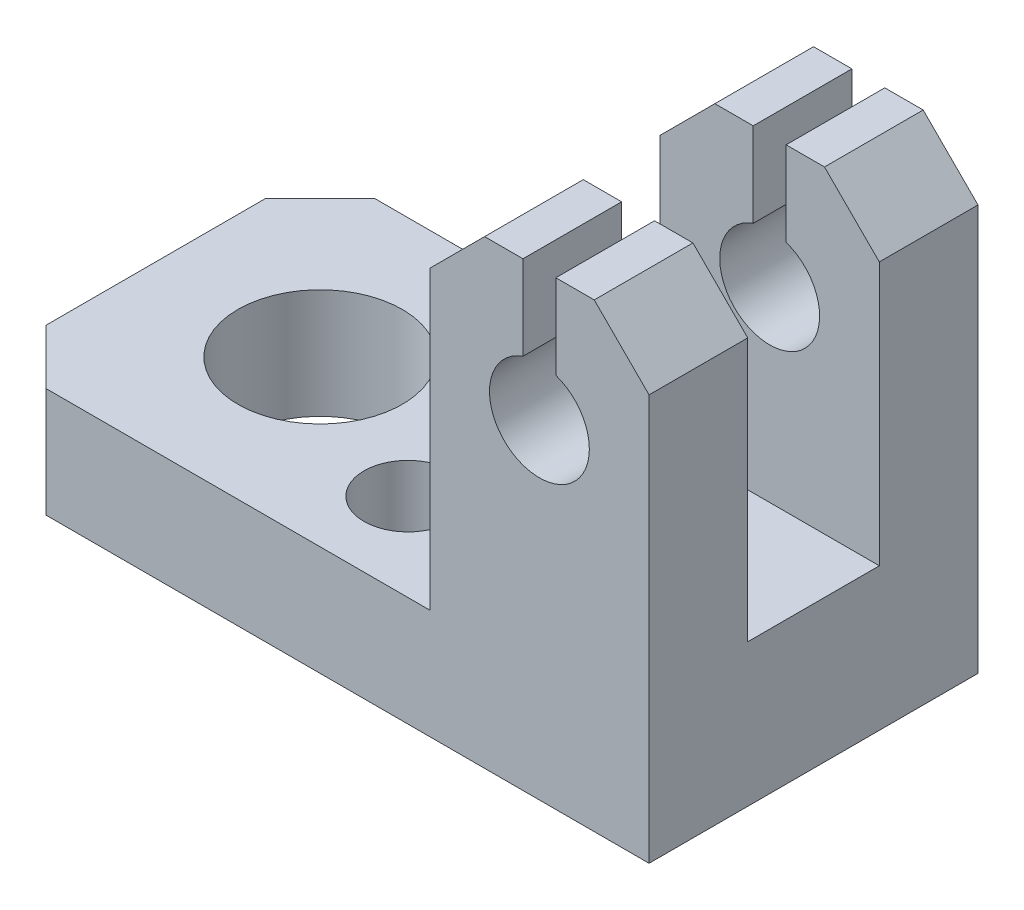
SolidWorks part; units mm, degrees
ref_plane "Front Plane" through (0, 0, 0) normal (0, 0, 1) x (1, 0, 0)
ref_plane "Top Plane" through (0, 0, 0) normal (0, 1, 0) x (1, 0, 0)
ref_plane "Right Plane" through (0, 0, 0) normal (1, 0, 0) x (0, 0, -1)
sketch "Sketch1" plane through (0, 0, 0) normal (0, 0, 1) x (1, 0, 0)
  line L0 (-11.5, 42) -> (-20, 42)
  line L1 (0, 0) -> (-60, 0)
  line L3 (-20, 10) -> (-60, 10)
  line L4 (-60, 0) -> (-60, 10)
  line L5 (0, 0) -> (-20, 0)
  line L6 (0, 0) -> (0, 42)
  line L7 (0, 42) -> (-8.5, 42)
  line L8 (-20, 10) -> (-20, 42)
  line L10 (-11.5, 42) -> (-11.5, 34.2993)
  line L12 (-8.5, 42) -> (-8.5, 34.2993)
  arc A0 (-11.5, 34.2993) -> (-8.5, 34.2993) centre (-10, 30) ccw
  dimension "D1" = 60
  dimension "D2" = 42
  dimension "D3" = 20
  dimension "D4" = 10
  dimension "D6" = 30
extrude "Boss-Extrude1" add sketch "Sketch1" along normal blind 30 contours A0 L10 L0 L8 L3 L4 L1 L6 L7 L12
sketch "Sketch2" plane through (0, 10, 0) normal (0, 1, 0) x (1, 0, 0)
  line L0 (-60, -15) -> (-17.2625, -15) construction
  line L1 (-60, -30) -> (-60, 0) construction
  line L2 (-30, -22) -> (-30, -8) construction
  line L3 (0, -30) -> (0, 0) construction
  circle A0 centre (-45, -15) radius 7.5
  circle A2 centre (-30, -8) radius 4
  circle A3 centre (-30, -22) radius 4
  point P9 (-30, -15)
  dimension "D1" = 15
  dimension "D3" = 8
  dimension "D2" = 45
  dimension "D4" = 14
  dimension "D5" = 30
extrude "Cut-Extrude1" cut sketch "Sketch2" against normal through all
sketch "Sketch3" plane through (-20, 0, 0) normal (-1, 0, 0) x (0, 0, 1)
  line L0 (30, 42) -> (0, 42) construction
  line L1 (9, 42) -> (21, 42)
  line L2 (9, 42) -> (9, 13)
  line L3 (9, 13) -> (21, 13)
  line L4 (21, 42) -> (21, 13)
  point P6 (15, 42)
  point P7 (15, 42)
  point P8 (21, 19.8827)
  dimension "D1" = 12
  dimension "D2" = 3
extrude "Cut-Extrude2" cut sketch "Sketch3" against normal through all
chamfer "Chamfer1" distance 5 angle 45 6 edges at (0, 42, 4.5) (0, 42, 25.5) (-20, 42, 25.5) (-20, 42, 4.5) (-60, 5, 30) (-60, 5, 0)
